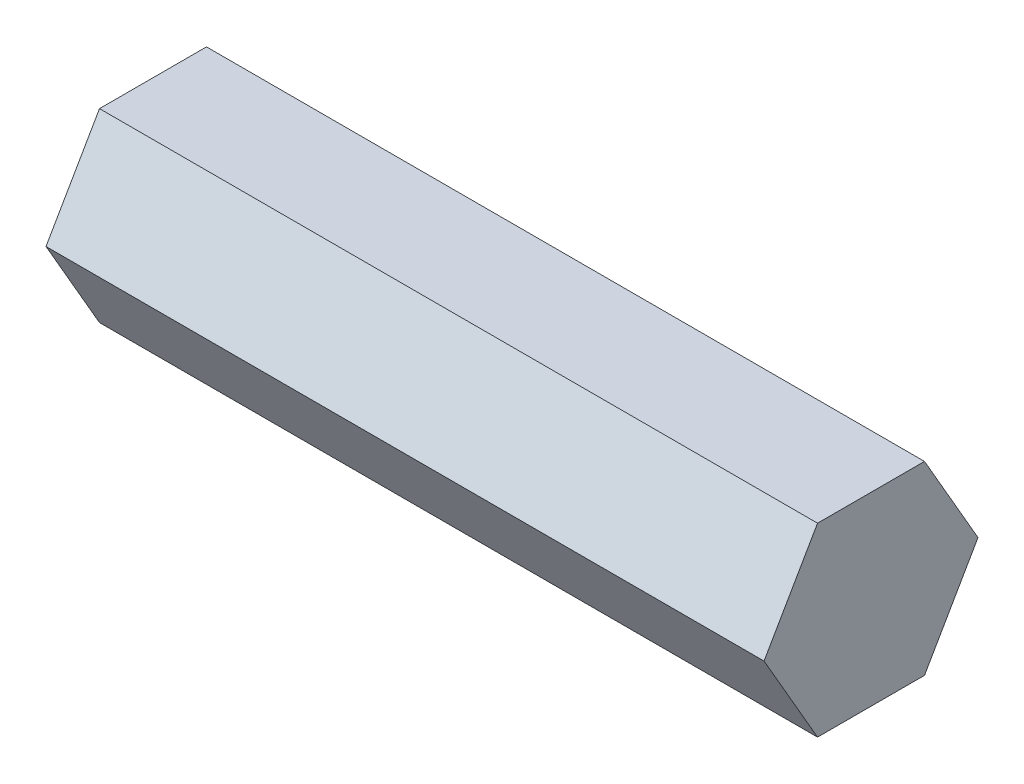
SolidWorks part; units mm, degrees
material "7075-T6 (SN)"
ref_plane "Front Plane" through (0, 0, 0) normal (0, 0, 1) x (1, 0, 0)
ref_plane "Top Plane" through (0, 0, 0) normal (0, 1, 0) x (1, 0, 0)
ref_plane "Right Plane" through (0, 0, 0) normal (1, 0, 0) x (0, 0, -1)
sketch "Sketch1" plane through (0, 0, 0) normal (1, 0, 0) x (0, 0, -1)
  line L7 (7.3323, 0) -> (3.6662, 6.35)
  line L8 (3.6662, 6.35) -> (-3.6662, 6.35)
  line L9 (-3.6662, 6.35) -> (-7.3323, 0)
  line L10 (-7.3323, 0) -> (-3.6662, -6.35)
  line L11 (-3.6662, -6.35) -> (3.6662, -6.35)
  line L12 (3.6662, -6.35) -> (7.3323, 0)
  circle A1 centre (0, 0) radius 6.35 construction
  dimension "D1" = 12.7
extrude "Boss-Extrude1" add sketch "Sketch1" along normal blind 49.2125
